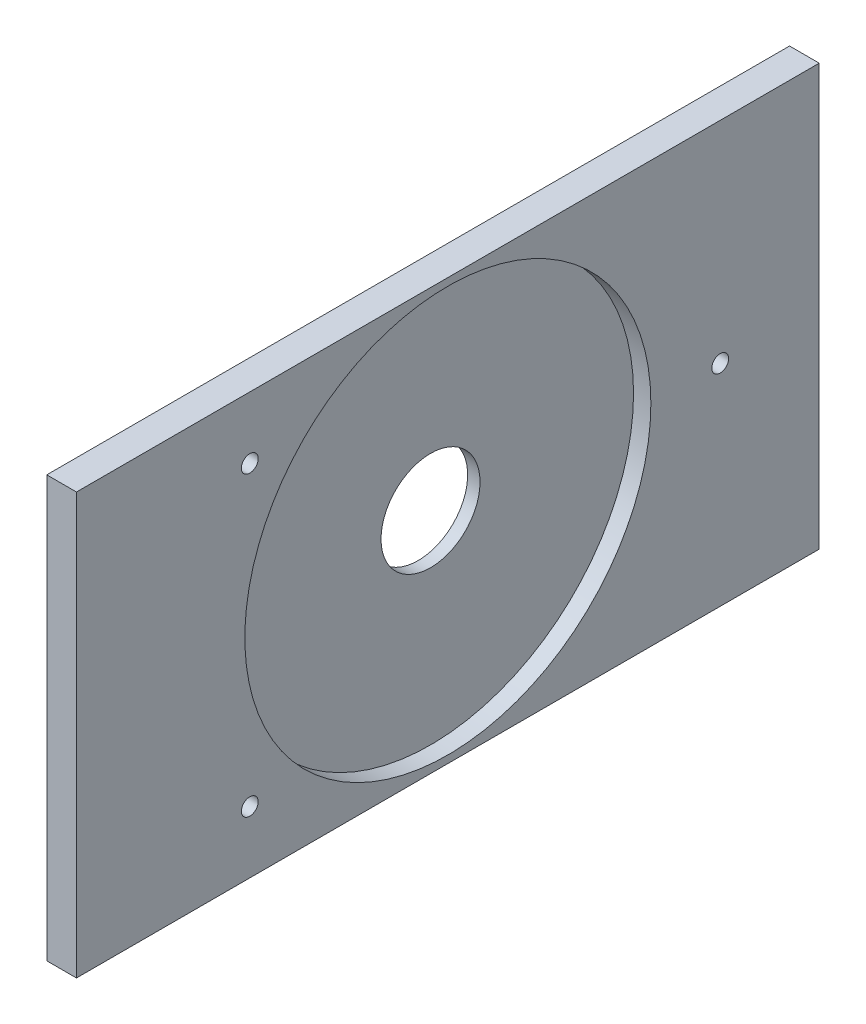
SolidWorks part; units mm, degrees
ref_plane "Front Plane" through (0, 0, 0) normal (0, 0, 1) x (1, 0, 0)
ref_plane "Top Plane" through (0, 0, 0) normal (0, 1, 0) x (1, 0, 0)
ref_plane "Right Plane" through (0, 0, 0) normal (1, 0, 0) x (0, 0, -1)
sketch "Sketch1" plane through (-34.2414, 0, 0) normal (-1, 0, 0) x (0, 0, 1)
  line L1 (386.3098, 523.9374) -> (536.3098, 523.9374)
  line L2 (386.3098, 523.9374) -> (386.3098, 438.9374)
  line L3 (386.3098, 438.9374) -> (536.3098, 438.9374)
  line L4 (536.3098, 523.9374) -> (536.3098, 438.9374)
extrude "Boss-Extrude1" add sketch "Sketch1" along normal blind 3.5 and the other way offset from surface (2.5 mm away) 0.5
sketch "Sketch4" plane through (-31.7414, 0, 0) normal (1, 0, 0) x (0, 0, -1)
  circle A0 centre (-461.3098, 481.4374) radius 41
  dimension "D1" = 82
extrude "Cut-Extrude2" cut sketch "Sketch4" against normal blind 3.5
sketch "Sketch5" plane through (-37.7414, 0, 0) normal (-1, 0, 0) x (0, 0, 1)
  circle A0 centre (461.3098, 481.4374) radius 10
  dimension "D1" = 20
extrude "Cut-Extrude3" cut sketch "Sketch5" against normal through all
sketch "Sketch8" plane through (-37.7414, 0, 0) normal (-1, 0, 0) x (0, 0, 1)
  circle A0 centre (501.3098, 511.4374) radius 1.7
  circle A1 centre (406.3098, 481.4374) radius 1.7
  circle A2 centre (501.3098, 451.4374) radius 1.7
  circle A3 centre (461.3098, 481.4374) radius 10 construction
  dimension "D1" = 3.4
  dimension "D2" = 3.4
  dimension "D3" = 3.4
  dimension "D4" = 40
  dimension "D5" = 40
  dimension "D6" = 30
  dimension "D7" = 30
  dimension "D8" = 55
extrude "Cut-Extrude5" cut sketch "Sketch8" against normal through all
